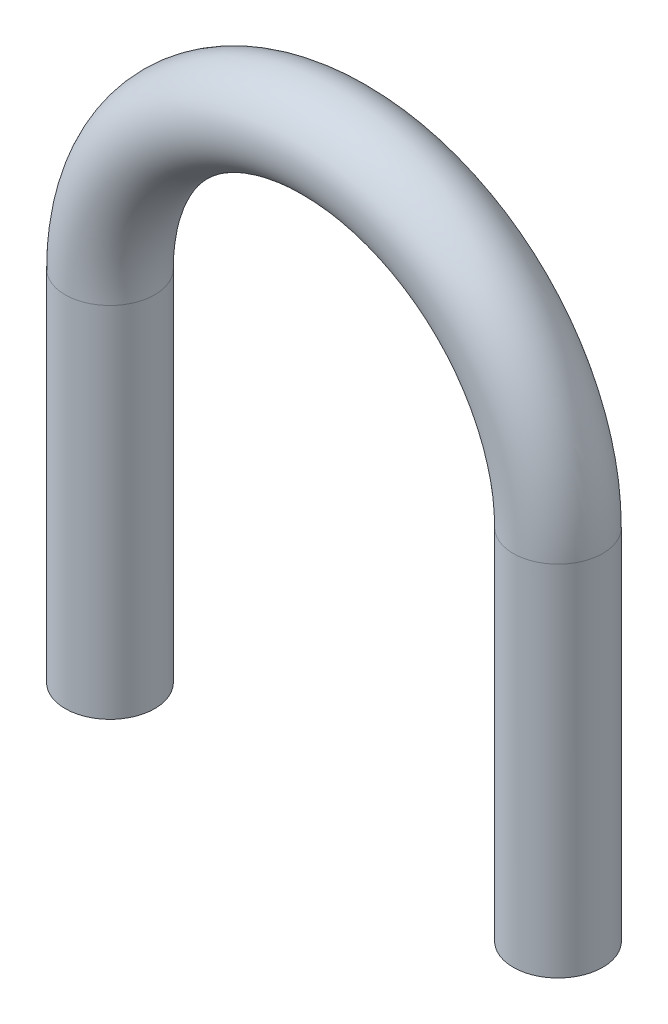
SolidWorks part; units mm, degrees
ref_plane "Front Plane" through (0, 0, 0) normal (0, 0, 1) x (1, 0, 0)
ref_plane "Top Plane" through (0, 0, 0) normal (0, 1, 0) x (1, 0, 0)
ref_plane "Right Plane" through (0, 0, 0) normal (1, 0, 0) x (0, 0, -1)
sketch "Sketch1" plane through (0, 0, 0) normal (0, 1, 0) x (1, 0, 0)
  line L0 (-10, 0) -> (0, 0) construction
  circle A0 centre (-10, 0) radius 2
  dimension "D1" = 4
  dimension "D2" = 10
sketch "Sketch2" plane through (0, 0, 0) normal (0, 0, 1) x (1, 0, 0)
  line L0 (-10, 0) -> (-10, 16)
  line L1 (-8, 0) -> (-12, 0) construction
  line L2 (10, 16) -> (10, 0)
  arc A0 (10, 16) -> (-10, 16) centre (0, 16) ccw
  dimension "D4" = 10
  dimension "D1" = 16
  dimension "D2" = 10
  dimension "D3" = 10
sweep "Sweep1" add profiles "Sketch1" path "Sketch2"
